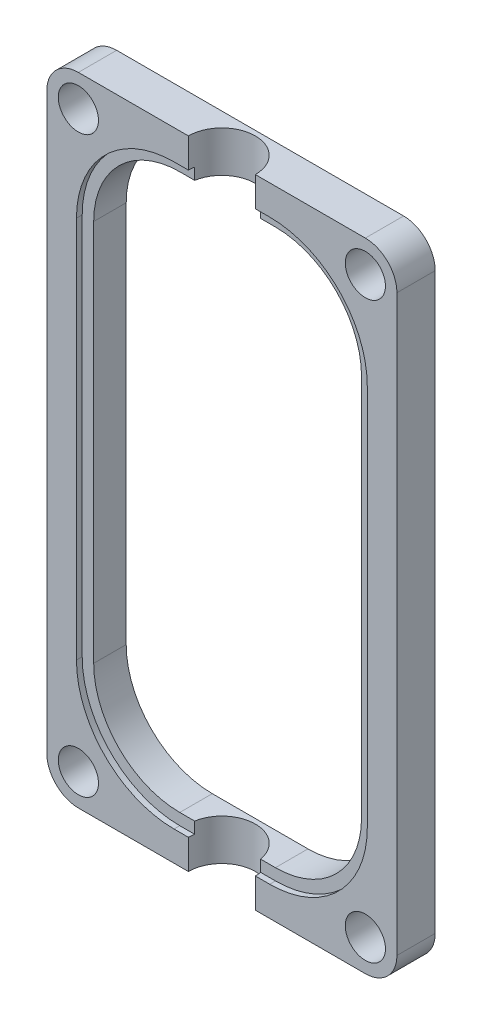
SolidWorks part; units mm, degrees
ref_plane "Ebene vorne" through (0, 0, 0) normal (1, 0, 0) x (0, 1, 0)
ref_plane "Ebene oben" through (0, 0, 0) normal (0, 0, 1) x (0, 1, 0)
ref_plane "Ebene rechts" through (0, 0, 0) normal (0, 1, 0) x (-1, 0, 0)
sketch "Skizze1" plane through (0, 0, 0) normal (0, 0, 1) x (0, 1, 0)
  line L0 (-16.65, 7.5) -> (-16.65, -7.5)
  line L1 (-15, -9.15) -> (15, -9.15)
  line L2 (16.65, -7.5) -> (16.65, 7.5)
  line L3 (15, 9.15) -> (-15, 9.15)
  line L4 (-14.5, 2.5) -> (-14.5, -2.5)
  line L5 (-15, 7.5) -> (15, 7.5) construction
  line L6 (-15, 7.5) -> (-15, -7.5) construction
  line L7 (-15, -7.5) -> (15, -7.5) construction
  line L8 (15, 7.5) -> (15, -7.5) construction
  line L9 (-10, -7) -> (10, -7)
  line L10 (14.5, -2.5) -> (14.5, 2.5)
  line L11 (10, 7) -> (-10, 7)
  line L12 (-10, 2.5) -> (10, 2.5) construction
  line L13 (10, 2.5) -> (10, -2.5) construction
  line L14 (10, -2.5) -> (-10, -2.5) construction
  line L15 (-10, -2.5) -> (-10, 2.5) construction
  arc A0 (-16.65, -7.5) -> (-15, -9.15) centre (-15, -7.5) ccw
  arc A1 (15, -9.15) -> (16.65, -7.5) centre (15, -7.5) ccw
  arc A2 (16.65, 7.5) -> (15, 9.15) centre (15, 7.5) ccw
  arc A3 (-15, 9.15) -> (-16.65, 7.5) centre (-15, 7.5) ccw
  arc A4 (-14.5, -2.5) -> (-10, -7) centre (-10, -2.5) ccw
  arc A5 (10, -7) -> (14.5, -2.5) centre (10, -2.5) ccw
  arc A6 (14.5, 2.5) -> (10, 7) centre (10, 2.5) ccw
  arc A7 (-10, 7) -> (-14.5, 2.5) centre (-10, 2.5) ccw
  circle A8 centre (-15, 7.5) radius 1.05
  circle A9 centre (15, 7.5) radius 1.05
  circle A10 centre (15, -7.5) radius 1.05
  circle A11 centre (-15, -7.5) radius 1.05
  point P12 (0, 2.5)
  point P13 (0, 7.5)
  point P14 (15, 0)
  point P28 (10, 0)
  dimension "D3" = 1.65
  dimension "D4" = 20
  dimension "D6" = 4.5
  dimension "D7" = 2.1
  dimension "D1" = 30
  dimension "D2" = 15
  dimension "D5" = 5
extrude "Aufsatz-Linear austragen1" add sketch "Skizze1" along normal blind 2
sketch "Skizze2" plane through (0, 0, 2) normal (0, 0, 1) x (1, 0, 0)
  line L8 (-2.5, -15.1) -> (2.5, -15.1)
  line L9 (7.6, -10) -> (7.6, 10)
  line L10 (2.5, 15.1) -> (-2.5, 15.1)
  line L11 (-7.6, 10) -> (-7.6, -10)
  line L12 (-2.5, -15.1) -> (2.5, -15.1)
  line L13 (7.6, -10) -> (7.6, 10)
  line L14 (2.5, 15.1) -> (-2.5, 15.1)
  line L15 (-7.6, 10) -> (-7.6, -10)
  arc A8 (-7.6, -10) -> (-2.5, -15.1) centre (-2.5, -10) ccw
  arc A9 (2.5, -15.1) -> (7.6, -10) centre (2.5, -10) ccw
  arc A10 (7.6, 10) -> (2.5, 15.1) centre (2.5, 10) ccw
  arc A11 (-2.5, 15.1) -> (-7.6, 10) centre (-2.5, 10) ccw
  arc A12 (-7.6, -10) -> (-2.5, -15.1) centre (-2.5, -10) ccw
  arc A13 (2.5, -15.1) -> (7.6, -10) centre (2.5, -10) ccw
  arc A14 (7.6, 10) -> (2.5, 15.1) centre (2.5, 10) ccw
  arc A15 (-2.5, 15.1) -> (-7.6, 10) centre (-2.5, 10) ccw
  dimension "D1" = 0.6
extrude "Schnitt-Linear austragen1" cut sketch "Skizze2" against normal blind 0.3
sketch "Skizze3" plane through (0, -16.65, 0) normal (0, -1, 0) x (1, 0, 0)
  line L0 (-1.75, 2) -> (1.75, 2)
  line L1 (0, 2) -> (0, 0) construction
  arc A0 (-1.75, 2) -> (1.75, 2) centre (0, 2) ccw
  dimension "D1" = 3.5
  dimension "D2" = 2
extrude "Schnitt-Linear austragen2" cut sketch "Skizze3" against normal up to surface (33.3 mm away) up to face at (0, 16.65, 1)
